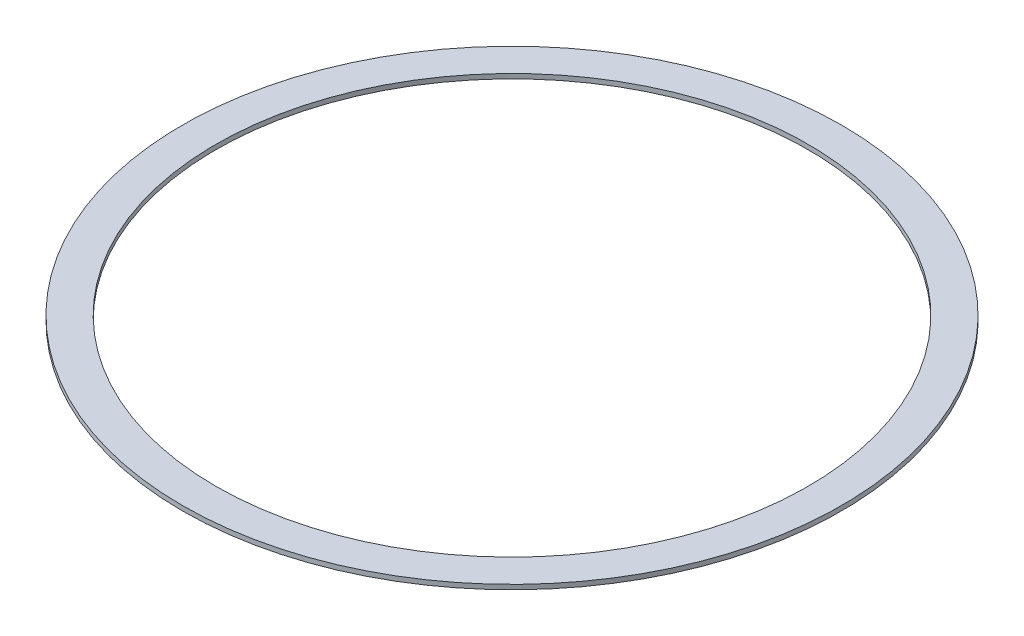
SolidWorks part; units mm, degrees
material "Duranickel(R) 301"
ref_plane "Front Plane" through (0, 0, 0) normal (0, 0, 1) x (1, 0, 0)
ref_plane "Top Plane" through (0, 0, 0) normal (0, 1, 0) x (1, 0, 0)
ref_plane "Right Plane" through (0, 0, 0) normal (1, 0, 0) x (0, 0, -1)
sketch "Sketch1" plane through (0, 0, 0) normal (0, 1, 0) x (1, 0, 0)
  circle A0 centre (0, 0) radius 160.909
  circle A1 centre (0, 0) radius 179.0446
  dimension "D1" = 358.0892
  dimension "D2" = 321.818
extrude "Boss-Extrude1" add sketch "Sketch1" along normal blind 2.54
ref_plane "Plane1" through (0, 1.27, 0) normal (0, 1, 0) x (1, 0, 0)
